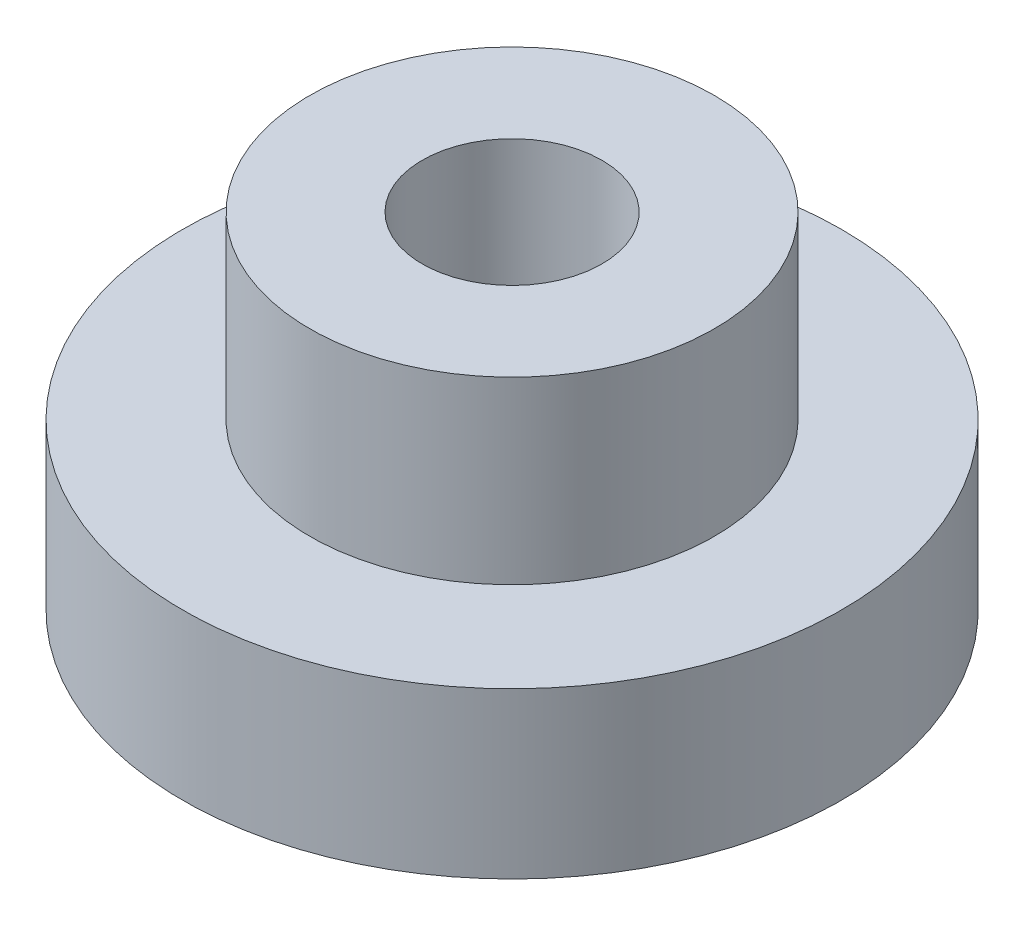
SolidWorks part; units mm, degrees
ref_plane "Front" through (0, 0, 0) normal (0, 0, 1) x (1, 0, 0)
ref_plane "Top" through (0, 0, 0) normal (0, 1, 0) x (1, 0, 0)
ref_plane "Right" through (0, 0, 0) normal (1, 0, 0) x (0, 0, -1)
sketch "Эскиз1" plane through (0, 0, 0) normal (0, 0, 1) x (1, 0, 0)
  line L0 (0, 0) -> (0, 6.9221) construction
  line L1 (6, 23) -> (6, 0)
  line L2 (6, 0) -> (22, 0)
  line L3 (22, 0) -> (22, 11)
  line L4 (22, 11) -> (13.5, 11)
  line L5 (13.5, 11) -> (13.5, 23)
  line L6 (13.5, 23) -> (6, 23)
  dimension "D1" = 44
  dimension "D2" = 12
  dimension "D3" = 23
  dimension "D4" = 12
  dimension "D5" = 27
revolve "Повернуть1" add sketch "Эскиз1" angle 360 about L0
